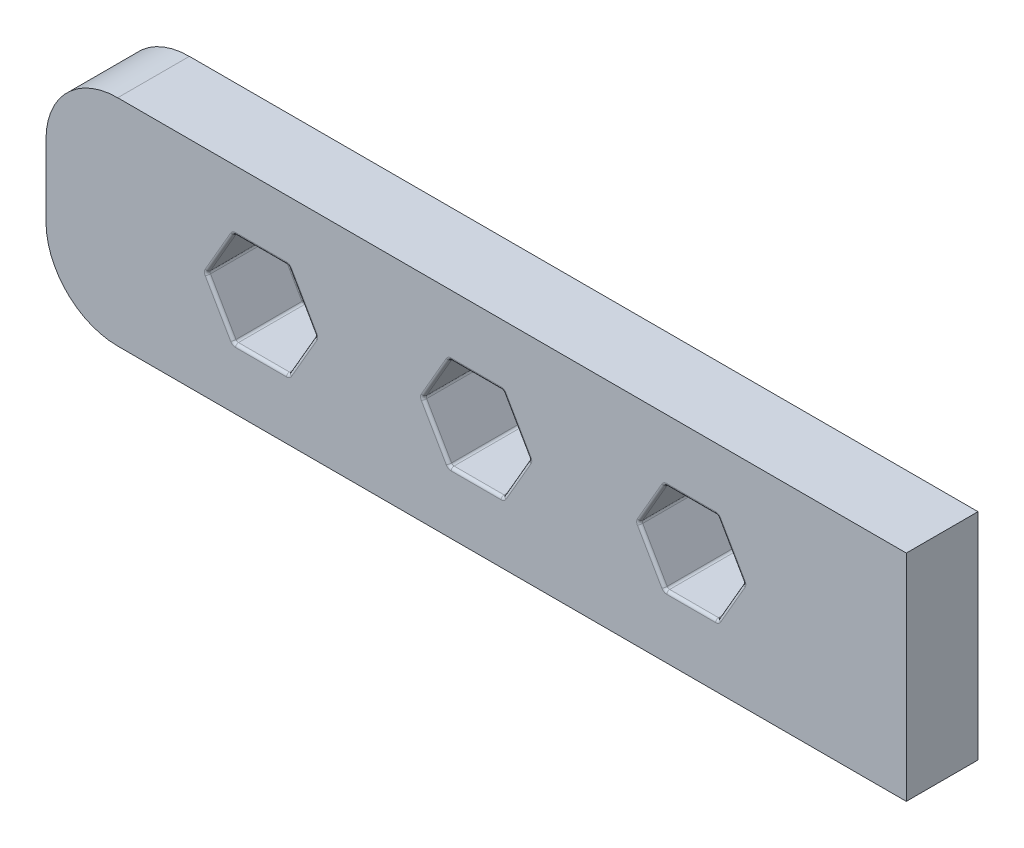
SolidWorks part; units mm, degrees
ref_plane "Front Plane" through (0, 0, 0) normal (0, 0, 1) x (1, 0, 0)
ref_plane "Top Plane" through (0, 0, 0) normal (0, 1, 0) x (1, 0, 0)
ref_plane "Right Plane" through (0, 0, 0) normal (1, 0, 0) x (0, 0, -1)
sketch "Sketch1" plane through (0, 0, 0) normal (0, 0, 1) x (1, 0, 0)
  line L1 (-25, -7.5) -> (30, -7.5)
  line L2 (-30, -2.5) -> (-30, 2.5)
  line L3 (-25, 7.5) -> (30, 7.5)
  line L4 (30, -7.5) -> (30, 7.5)
  line L5 (-30, -7.5) -> (30, 7.5) construction
  line L6 (-30, 7.5) -> (30, -7.5) construction
  arc A0 (-25, -7.5) -> (-30, -2.5) centre (-25, -2.5) cw
  arc A1 (-30, 2.5) -> (-25, 7.5) centre (-25, 2.5) cw
  point P0 (0, 0)
  dimension "D1" = 5
  dimension "D2" = 55
  dimension "D3" = 15
extrude "Boss-Extrude1" add sketch "Sketch1" along normal blind 5
sketch "Sketch2" plane through (0, 0, 0) normal (0, 0, 1) x (1, 0, 0)
  line L1 (-11.2184, 0) -> (-13.1092, 3.275)
  line L2 (-13.1092, 3.275) -> (-16.8908, 3.275)
  line L3 (-16.8908, 3.275) -> (-18.7816, 0)
  line L4 (-18.7816, 0) -> (-16.8908, -3.275)
  line L5 (-16.8908, -3.275) -> (-13.1092, -3.275)
  line L6 (-13.1092, -3.275) -> (-11.2184, 0)
  line L7 (3.7095, 0) -> (1.8547, 3.2125)
  line L8 (1.8547, 3.2125) -> (-1.8547, 3.2125)
  line L9 (-1.8547, 3.2125) -> (-3.7095, 0)
  line L10 (-3.7095, 0) -> (-1.8547, -3.2125)
  line L11 (-1.8547, -3.2125) -> (1.8547, -3.2125)
  line L12 (1.8547, -3.2125) -> (3.7095, 0)
  line L13 (18.6373, 0) -> (16.8187, 3.15)
  line L14 (16.8187, 3.15) -> (13.1813, 3.15)
  line L15 (13.1813, 3.15) -> (11.3627, 0)
  line L16 (11.3627, 0) -> (13.1813, -3.15)
  line L17 (13.1813, -3.15) -> (16.8187, -3.15)
  line L18 (16.8187, -3.15) -> (18.6373, 0)
  circle A0 centre (-15, 0) radius 3.275 construction
  circle A1 centre (0, 0) radius 3.2125 construction
  circle A2 centre (15, 0) radius 3.15 construction
  dimension "D1" = 6.3
  dimension "D2" = 6.425
  dimension "D3" = 6.55
  dimension "D4" = 15
  dimension "D5" = 15
extrude "Cut-Extrude3" cut sketch "Sketch2" along normal blind 5
fillet "Fillet1" radius 0.2 54 edges at (15, 3.15, 5) (15, 3.15, 0) (17.728, -1.575, 5) (17.728, -1.575, 0) (12.272, -1.575, 5) (12.272, -1.575, 0) (0, 3.2125, 5) (0, 3.2125, 0) (2.7821, -1.6062, 5) (2.7821, -1.6062, 0) (-2.7821, -1.6062, 5) (-2.7821, -1.6062, 0) (-15, 3.275, 5) (-15, 3.275, 0) (-12.1638, -1.6375, 5) (-12.1638, -1.6375, 0) (-17.8362, -1.6375, 5) (-17.8362, -1.6375, 0) (11.3627, 0, 2.5) (12.272, 1.575, 5) (13.1813, 3.15, 2.5) (12.272, 1.575, 0) (16.8187, 3.15, 2.5) (17.728, 1.575, 5) (18.6373, 0, 2.5) (17.728, 1.575, 0) (16.8187, -3.15, 2.5) (15, -3.15, 5) (13.1813, -3.15, 2.5) (15, -3.15, 0) (-3.7095, 0, 2.5) (-2.7821, 1.6063, 5) (-1.8547, 3.2125, 2.5) (-2.7821, 1.6063, 0) (1.8547, 3.2125, 2.5) (2.7821, 1.6063, 5) (3.7095, 0, 2.5) (2.7821, 1.6063, 0) (1.8547, -3.2125, 2.5) (0, -3.2125, 5) (-1.8547, -3.2125, 2.5) (0, -3.2125, 0) (-18.7816, 0, 2.5) (-17.8362, 1.6375, 5) (-16.8908, 3.275, 2.5) (-17.8362, 1.6375, 0) (-13.1092, 3.275, 2.5) (-12.1638, 1.6375, 5) (-11.2184, 0, 2.5) (-12.1638, 1.6375, 0) (-13.1092, -3.275, 2.5) (-15, -3.275, 5) (-16.8908, -3.275, 2.5) (-15, -3.275, 0)
